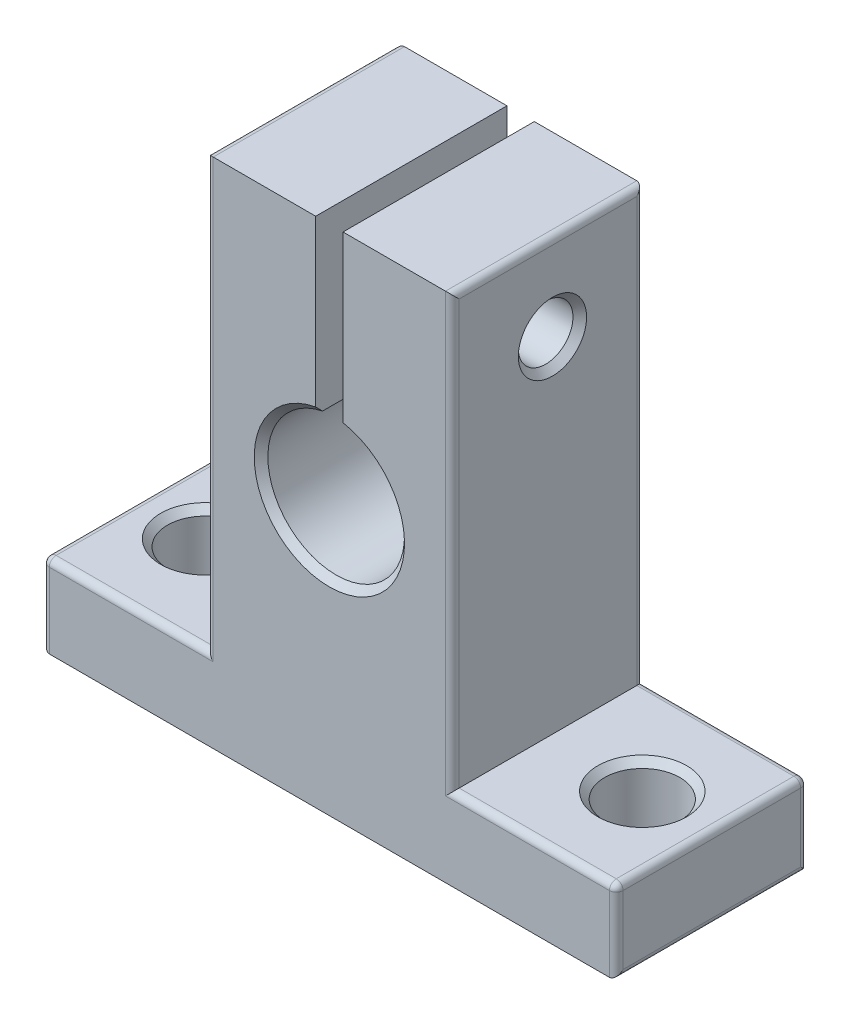
SolidWorks part; units mm, degrees
material "1060 Alloy"
ref_plane "Front Plane" through (0, 0, 0) normal (0, 0, 1) x (1, 0, 0)
ref_plane "Top Plane" through (0, 0, 0) normal (0, 1, 0) x (1, 0, 0)
ref_plane "Right Plane" through (0, 0, 0) normal (1, 0, 0) x (0, 0, -1)
sketch "Sketch1" plane through (0, 0, 0) normal (0, 0, 1) x (1, 0, 0)
  line L0 (0, 0) -> (-50000, 0) construction
  line L1 (0, 0) -> (0, 50000) construction
  line L2 (-21, -3) -> (-21, 3)
  line L3 (-21, 3) -> (-9, 3)
  line L4 (-9, 3) -> (-9, 34.5)
  line L5 (-9, 34.5) -> (-1, 34.5)
  line L6 (9, 34.5) -> (9, 3)
  line L7 (9, 3) -> (21, 3)
  line L8 (21, 3) -> (21, -3)
  line L9 (21, -3) -> (-21, -3)
  line L10 (16, -3) -> (16, 3) construction
  line L11 (-16, -3) -> (-16, 3) construction
  line L12 (-1, 34.5) -> (-1, 21.899)
  line L13 (1, 34.5) -> (1, 21.899)
  line L14 (1, 34.5) -> (9, 34.5)
  arc A0 (-1, 21.899) -> (1, 21.899) centre (0, 17) ccw
  point P8 (-21, 0)
  point P15 (0, -3)
  point P21 (16, 0)
  dimension "Shaft Diameter" = 10
  dimension "W" = 42
  dimension "P" = 18
  dimension "F" = 37.5
  dimension "G" = 6
  dimension "B" = 32
  dimension "D1" = 2
  dimension "h" = 20
extrude "Boss-Extrude1" add sketch "Sketch1" along normal mid plane 14
sketch "Sketch2" plane through (0, 3, 0) normal (0, 1, 0) x (1, 0, 0)
  line L0 (0, 0) -> (50000, 0) construction
  line L1 (0.3141, 0) -> (-49999.6859, 0) construction
  line L2 (-0.0955, 2.4842) -> (-0.0955, 50002.4842) construction
  circle A0 centre (15.9045, 0) radius 2.75
  circle A1 centre (-16.0955, 0) radius 2.75
  dimension "B" = 32
  dimension "S" = 5.5
extrude "Cut-Extrude1" cut sketch "Sketch2" against normal through all
sketch "Sketch5" plane through (-1, 0, 0) normal (1, 0, 0) x (0, 0, -1)
  line L0 (-7, 28.1995) -> (7, 28.1995) construction
  line L1 (7, 21.899) -> (7, 34.5) construction
  line L2 (0, 34.5) -> (0, 21.899) construction
  line L3 (-7, 34.5) -> (7, 34.5) construction
  line L4 (-7, 21.899) -> (7, 21.899) construction
  line L5 (-7, 21.899) -> (-7, 34.5) construction
  circle A0 centre (0.3307, 28.1995) radius 2
  dimension "Clamping bold" = 4
extrude "Cut-Extrude2" cut sketch "Sketch5" against normal through all both and the other way through all
chamfer "Chamfer2" distance 0.5 angle 45 6 edges at (0, 12, -7) (0, 12, 7) (-9, 28.1995, -2.3307) (-13.3455, 3, 0) (9, 28.1995, 1.6693) (13.1545, 3, 0)
fillet "Fillet2" radius 0.5 18 edges at (21, -3, 0) (21, 0, 7) (21, 3, 0) (21, 0, -7) (-21, 3, 0) (-21, 0, 7) (-21, -3, 0) (-21, 0, -7) (-15, 3, -7) (-15, 3, 7) (-9, 18.75, 7) (-9, 34.5, 0) (-9, 18.75, -7) (9, 18.75, -7) (9, 18.75, 7) (15, 3, 7) (15, 3, -7) (9, 34.5, 0)
equation "\"W\"= \"W@Sketch1\"'Width"
equation "\"B\"= \"B@Sketch1\"'between hold"
equation "\"F\"= \"F@Sketch1\"'Hight"
equation "\"P\"= \"P@Sketch1\""
equation "\"G\"= \"G@Sketch1\""
equation "\"Shaft diameter\"= \"Shaft Diameter@Sketch1\""
equation "\"S\"= 5.5'M5"
equation "\"Clamping bold\"= 4'M4"
equation "\"h\"= \"h@Sketch1\""
